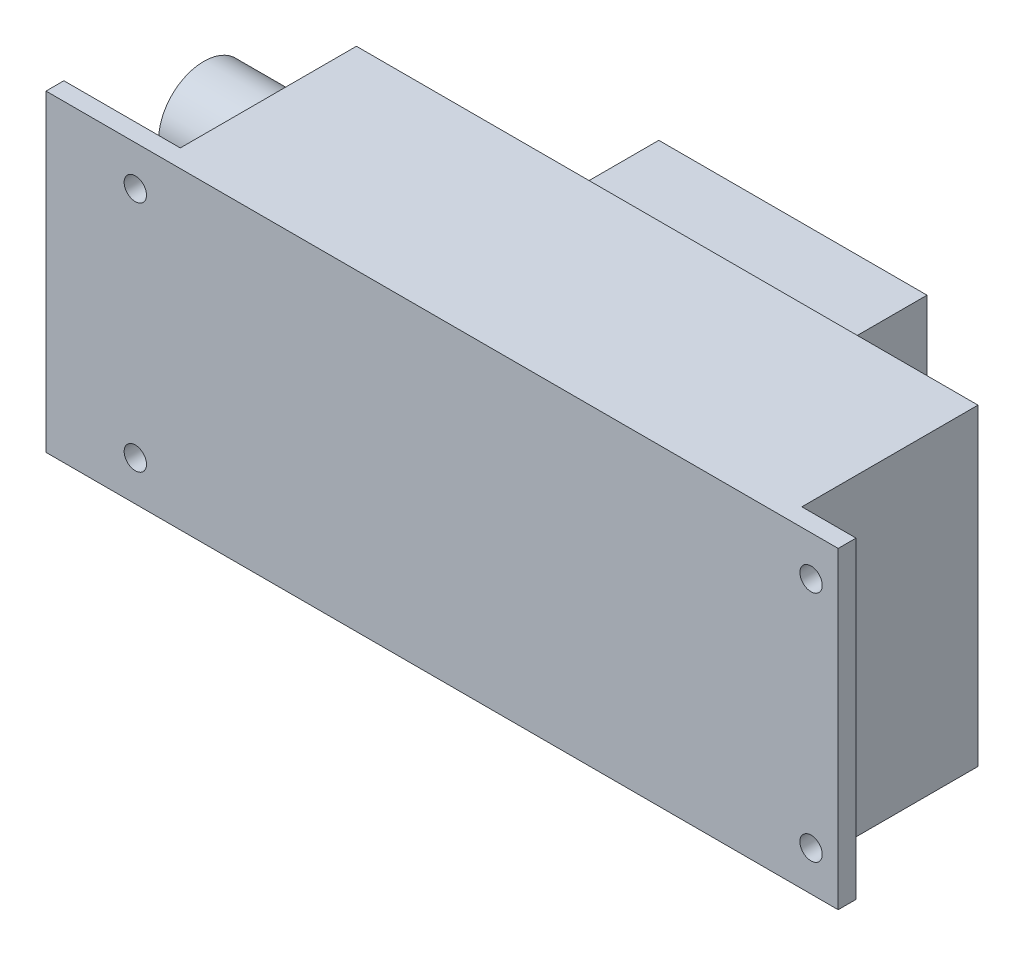
SolidWorks part; units mm, degrees
ref_plane "Front Plane" through (0, 0, 0) normal (0, 0, 1) x (1, 0, 0)
ref_plane "Top Plane" through (0, 0, 0) normal (0, 1, 0) x (1, 0, 0)
ref_plane "Right Plane" through (0, 0, 0) normal (1, 0, 0) x (0, 0, -1)
sketch "Sketch1" plane through (0, 0, 0) normal (0, 0, 1) x (1, 0, 0)
  line L1 (0, 0) -> (88.6, 0)
  line L2 (0, 0) -> (0, 35)
  line L3 (0, 35) -> (88.6, 35)
  line L4 (88.6, 0) -> (88.6, 35)
  dimension "D1" = 88.6
  dimension "D2" = 35
extrude "Boss-Extrude1" add sketch "Sketch1" along normal blind 32
sketch "Sketch2" plane through (0, 0, 32) normal (0, 0, 1) x (1, 0, 0)
  line L3 (0, 35) -> (0, 0) construction
  line L5 (88.6, 0) -> (88.6, 35) construction
  point P0 (9.99, 30.535)
  point P1 (9.99, 4.465)
  point P2 (85.57, 4.465)
  point P3 (85.57, 30.535)
  point P4 (0, 0)
  point P5 (0, 0)
  point P6 (0, 0)
  point P7 (0, 0)
  point P8 (0, 0)
  point P9 (0, 0)
  point P16 (0, 17.5)
  dimension "D1" = 75.58
  dimension "D2" = 26.07
  dimension "D3" = 13.035
  dimension "D4" = 3.03
hole_wizard "Tap Drill for M3x0.5 Tap1" positions "Sketch2" profile "Sketch3" hole size "M3x0.5" standard "ANSI Metric" end condition through all
sketch "Sketch3" plane through (9.99, 30.535, 32) normal (1, 0, 0) x (0, -1, 0)
  line L0 (0, 0) -> (0, 32)
  line L1 (0, 32) -> (1.25, 32)
  line L2 (1.25, 32) -> (1.25, 0)
  line L5 (1.25, 0) -> (0, 0)
  line L11 (0, -6.35) -> (0, 107.95) construction
  dimension "Thru Hole Dia." = 2.5
  dimension "Thru Hole Depth" = 32
sketch "Sketch4" plane through (0, 0, 0) normal (0, 0, -1) x (-1, 0, 0)
  line L0 (0, 0) -> (-88.6, 0) construction
  line L1 (-88.6, 35) -> (-82.54, 35)
  line L2 (-88.6, 35) -> (-88.6, 0)
  line L3 (-88.6, 0) -> (-82.54, 0)
  line L4 (-82.54, 35) -> (-82.54, 0)
  line L5 (0, 35) -> (0, 0) construction
  line L6 (0, 35) -> (-13.02, 35)
  line L7 (0, 35) -> (0, 0)
  line L8 (0, 0) -> (-13.02, 0)
  line L9 (-13.02, 35) -> (-13.02, 0)
  line L10 (-88.6, 35) -> (0, 35) construction
  point P12 (0, 35)
  dimension "D1" = 6.06
extrude "Cut-Extrude2" cut sketch "Sketch4" against normal blind 30
sketch "Sketch5" plane through (0, 0, 0) normal (0, 0, -1) x (-1, 0, 0)
  line L0 (-82.54, 0) -> (-82.54, 35) construction
  line L1 (-66.54, 32.5) -> (-36.54, 32.5)
  line L2 (-66.54, 32.5) -> (-66.54, 2.5)
  line L3 (-66.54, 2.5) -> (-36.54, 2.5)
  line L4 (-36.54, 32.5) -> (-36.54, 2.5)
  line L5 (-82.54, 0) -> (-82.54, 35) construction
  point P8 (-82.54, 17.5)
  dimension "D1" = 16
  dimension "D2" = 30
  dimension "D3" = 30
  dimension "D4" = 15
extrude "Cut-Extrude3" cut sketch "Sketch5" against normal blind 10.3 flip side to cut
sketch "Sketch6" plane through (13.02, 0, 0) normal (-1, 0, 0) x (0, 0, 1)
  line L0 (14.35, 24.005) -> (14.35, 10.995) construction
  line L1 (19.4, 24.005) -> (19.4, 10.995)
  line L2 (9.3, 24.005) -> (9.3, 10.995)
  line L3 (10.3, 2.5) -> (10.3, 32.5) construction
  line L4 (10.3, 0) -> (10.3, 35) construction
  arc A0 (19.4, 24.005) -> (9.3, 24.005) centre (14.35, 24.005) ccw
  arc A1 (9.3, 10.995) -> (19.4, 10.995) centre (14.35, 10.995) ccw
  point P2 (14.35, 17.5)
  point P7 (14.35, 5.945)
  point P8 (14.35, 29.055)
  point P11 (10.3, 17.5)
  dimension "D1" = 23.11
  dimension "D2" = 10.1
  dimension "D3" = 1
extrude "Boss-Extrude2" add sketch "Sketch6" along normal up to surface (13.02 mm away) up to face at (0, 17.5, 31)
equation "\"D3@Sketch2\"=\"D2@Sketch2\"/2"
